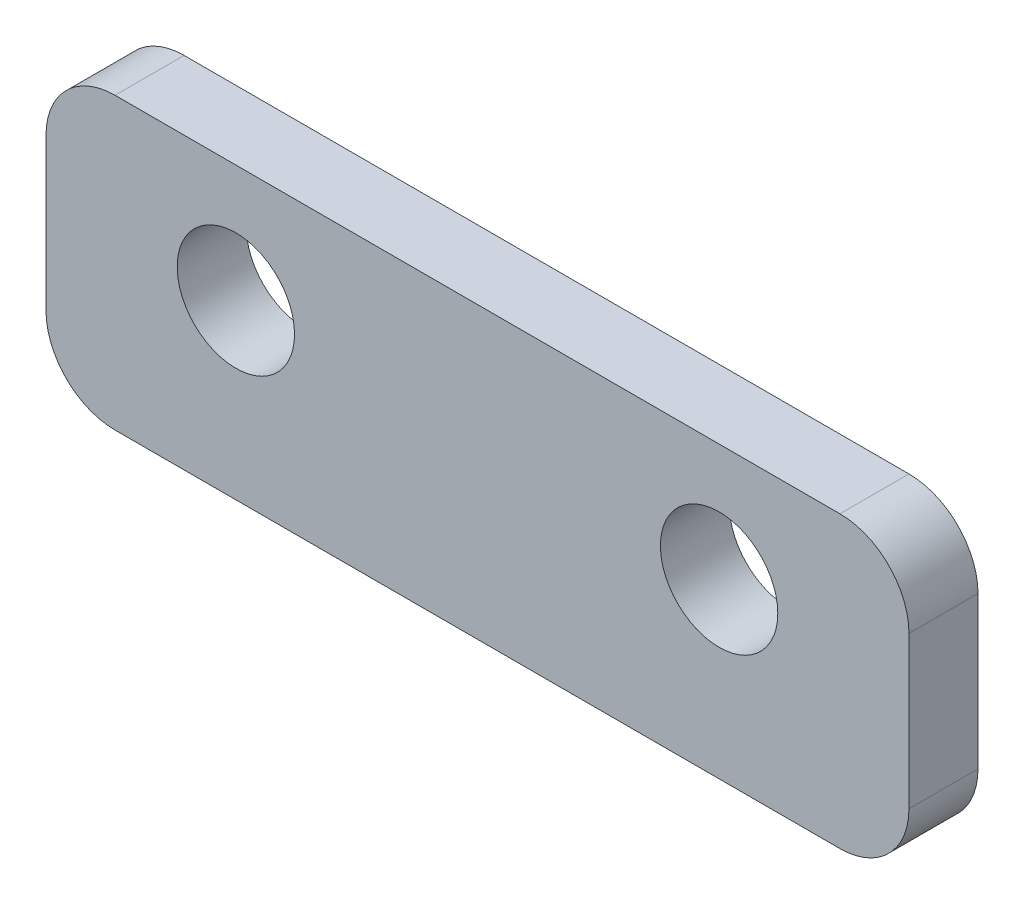
SolidWorks part; units mm, degrees
material "AISI 1020"
ref_plane "Front Plane" through (0, 0, 0) normal (0, 0, 1) x (1, 0, 0)
ref_plane "Top Plane" through (0, 0, 0) normal (0, 1, 0) x (1, 0, 0)
ref_plane "Right Plane" through (0, 0, 0) normal (1, 0, 0) x (0, 0, -1)
sketch "Sketch1" plane through (0, 0, 0) normal (0, 0, 1) x (1, 0, 0)
  line L1 (-12.5, -5) -> (12.5, -5)
  line L2 (-12.5, -5) -> (-12.5, 5)
  line L3 (-12.5, 5) -> (12.5, 5)
  line L4 (12.5, -5) -> (12.5, 5)
  line L5 (-12.5, -5) -> (12.5, 5) construction
  line L6 (-12.5, 5) -> (12.5, -5) construction
  point P0 (0, 0)
  dimension "D1" = 10
  dimension "D2" = 25
extrude "Boss-Extrude1" add sketch "Sketch1" along normal blind 2
hole_wizard "M3 Clearance Hole1" positions "Sketch2" profile "Sketch3" hole size "M3" standard "ANSI Metric" end condition through all
sketch "Sketch2" plane through (0, 0, 2) normal (0, 0, 1) x (1, 0, 0)
  line L0 (12.5, 5) -> (-12.5, 5) construction
  point P0 (-7, 0)
  point P2 (7, 0)
  dimension "D1" = 7
  dimension "D2" = 7
  dimension "D3" = 5
  dimension "D4" = 5
sketch "Sketch3" plane through (-7, 0, 2) normal (1, 0, 0) x (0, -1, 0)
  line L0 (0, 0) -> (0, 2)
  line L1 (0, 2) -> (1.7, 2)
  line L2 (1.7, 2) -> (1.7, 0)
  line L5 (1.7, 0) -> (0, 0)
  line L11 (0, -6.35) -> (0, 107.95) construction
  dimension "Thru Hole Dia." = 3.4
  dimension "Thru Hole Depth" = 2
sketch "Sketch4" plane through (0, -5, 0) normal (0, -1, 0) x (1, 0, 0)
  line L0 (-12.5, 2) -> (12.5, 2) construction
  line L1 (16.6361, 0) -> (-17.8659, 0)
  line L2 (16.6361, 0) -> (16.6361, 2)
  line L3 (16.6361, 2) -> (-17.8659, 2)
  line L4 (-17.8659, 0) -> (-17.8659, 2)
  line L5 (-12.5, 0) -> (12.5, 0) construction
sketch "Sketch5" plane through (0, 5, 0) normal (0, 1, 0) x (1, 0, 0)
  line L1 (12.5, 0) -> (-12.5, 0)
  line L2 (12.5, 0) -> (12.5, -2)
  line L3 (12.5, -2) -> (-12.5, -2)
  line L4 (-12.5, 0) -> (-12.5, -2)
extrude "Cut-Extrude1" cut sketch "Sketch5" against normal blind 1.6
fillet "Fillet1" radius 2 4 edges at (12.5, -5, 1) (-12.5, -5, 1) (-12.5, 3.4, 1) (12.5, 3.4, 1)
